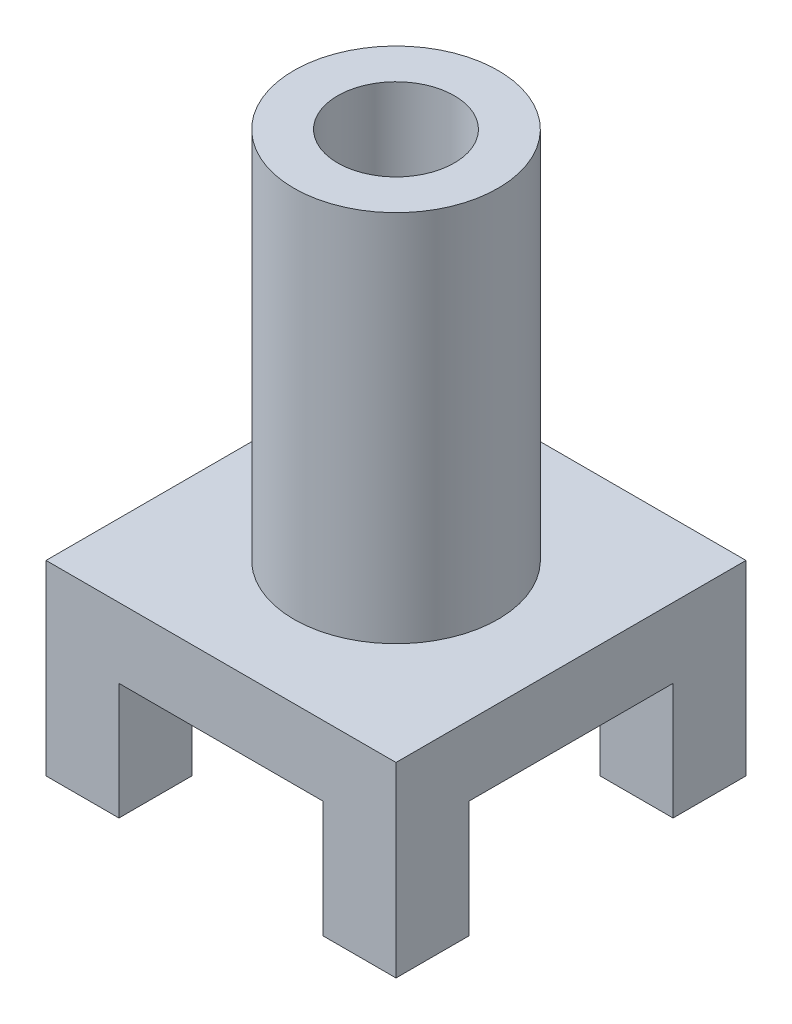
SolidWorks part; units mm, degrees
ref_plane "Alzado" through (0, 0, 0) normal (0, 0, 1) x (1, 0, 0)
ref_plane "Planta" through (0, 0, 0) normal (0, 1, 0) x (1, 0, 0)
ref_plane "Vista lateral" through (0, 0, 0) normal (1, 0, 0) x (0, 0, -1)
sketch "Croquis1" plane through (0, 0, 0) normal (0, 1, 0) x (1, 0, 0)
  line L5 (30, 30) -> (-30, 30)
  line L6 (30, 30) -> (30, -30)
  line L7 (30, -30) -> (-30, -30)
  line L8 (-30, 30) -> (-30, -30)
  line L9 (30, 30) -> (-30, -30) construction
  line L10 (30, -30) -> (-30, 30) construction
  point P0 (0, 0)
  dimension "D1" = 60
  dimension "D2" = 60
extrude "Saliente-Extruir1" add sketch "Croquis1" along normal blind 32 contours L6 L5 L8 L7
sketch "Croquis2" plane through (30, 0, 0) normal (1, 0, 0) x (0, 0, -1)
  line L0 (30, 0) -> (-30, 0) construction
  line L1 (-17.5, 0) -> (17.5, 0)
  line L2 (-17.5, 0) -> (-17.5, 20)
  line L3 (-17.5, 20) -> (17.5, 20)
  line L4 (17.5, 0) -> (17.5, 20)
  dimension "D1" = 35
  dimension "D2" = 20
extrude "Cortar-Extruir1" cut sketch "Croquis2" against normal through all
sketch "Croquis3" plane through (0, 0, 30) normal (0, 0, 1) x (1, 0, 0)
  line L5 (30, 0) -> (-30, 0) construction
  line L6 (-17.5, 0) -> (17.5, 0)
  line L7 (-17.5, 0) -> (-17.5, 20)
  line L8 (-17.5, 20) -> (17.5, 20)
  line L9 (17.5, 0) -> (17.5, 20)
  dimension "D1" = 20
  dimension "D2" = 35
  dimension "D3" = 17.5
extrude "Cortar-Extruir2" cut sketch "Croquis3" against normal through all
sketch "Croquis4" plane through (0, 32, 0) normal (0, 1, 0) x (1, 0, 0)
  circle A0 centre (0, 0) radius 17.5
  dimension "D1" = 35
extrude "Saliente-Extruir2" add sketch "Croquis4" along normal blind 64 contours A0
sketch "Croquis5" plane through (0, 96, 0) normal (0, 1, 0) x (1, 0, 0)
  circle A0 centre (0, 0) radius 10
  dimension "D1" = 20
extrude "Cortar-Extruir5" cut sketch "Croquis5" against normal through all contours A0
